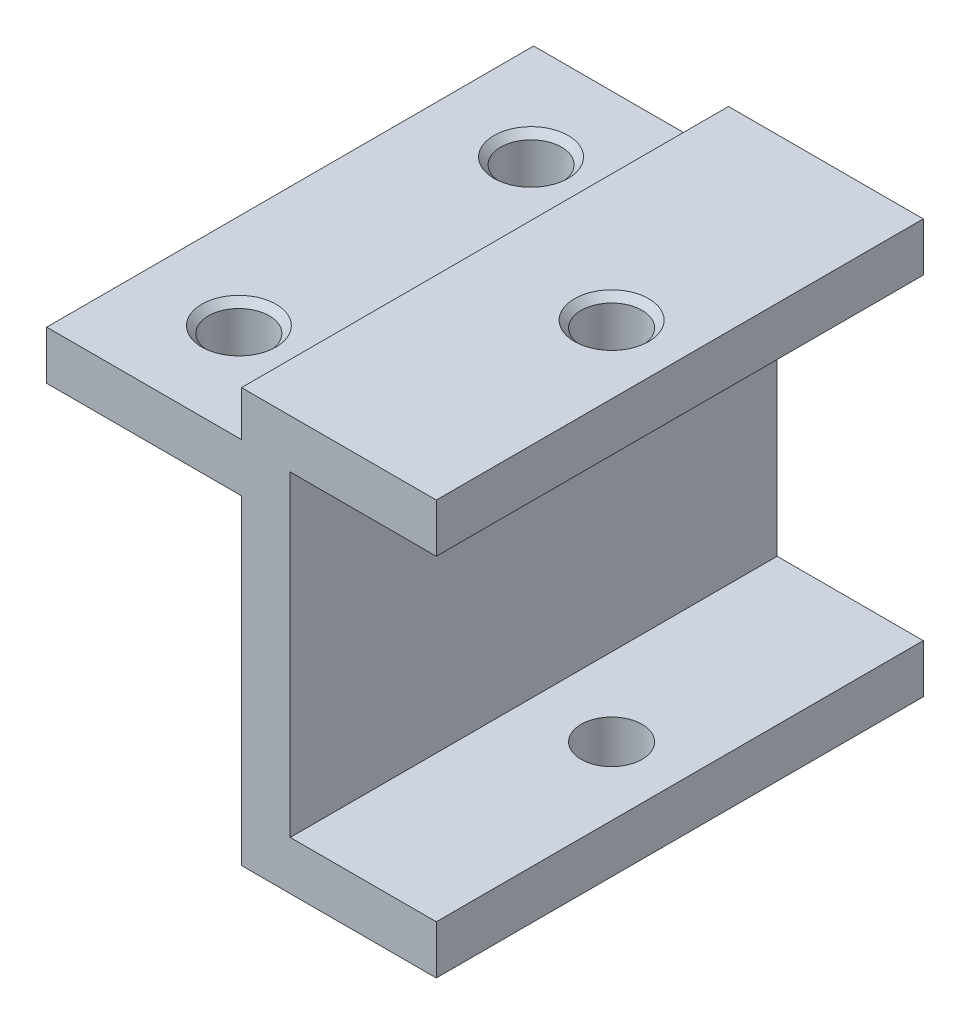
SolidWorks part; units mm, degrees
ref_plane "Front Plane" through (0, 0, 0) normal (0, 0, 1) x (1, 0, 0)
ref_plane "Top Plane" through (0, 0, 0) normal (0, 1, 0) x (1, 0, 0)
ref_plane "Right Plane" through (0, 0, 0) normal (1, 0, 0) x (0, 0, -1)
sketch "Sketch1" plane through (0, 0, 0) normal (0, 0, 1) x (1, 0, 0)
  line L0 (2, 5.1) -> (4, 5.1)
  line L1 (-4, -9.9) -> (4, -9.9)
  line L2 (-4, -9.9) -> (-4, 3.25)
  line L3 (-4, 7.1) -> (4, 7.1)
  line L7 (-2, -7.9) -> (2, -7.9)
  line L8 (-2, -7.9) -> (-2, 5.1)
  line L9 (-2, 5.1) -> (2, 5.1)
  line L10 (-4, 5.25) -> (-4, 7.1)
  line L11 (4, 5.1) -> (4, 7.1)
  line L12 (2, -7.9) -> (4, -7.9)
  line L13 (4, -7.9) -> (4, -9.9)
  line L14 (-4, 5.25) -> (-12, 5.25)
  line L16 (-4, 3.25) -> (-12, 3.25)
  line L17 (-12, 5.25) -> (-12, 3.25)
  dimension "D1" = 8
  dimension "D2" = 17
  dimension "D3" = 4
  dimension "D4" = 13
  dimension "D5" = 2
  dimension "D6" = 8
  dimension "D7" = 1.85
extrude "Boss-Extrude1" add sketch "Sketch1" along normal blind 20
sketch "Sketch2" plane through (0, 5.25, 0) normal (0, 1, 0) x (1, 0, 0)
  line L0 (-4, 0) -> (-12, 0) construction
  line L1 (-4, -20) -> (-12, -20) construction
  point P0 (-8.1084, -4)
  point P1 (-8.1084, -16)
  dimension "D1" = 4
  dimension "D2" = 4
hole_wizard "M3 Tapped Hole1" positions "3DSketch1" profile "Sketch3" tap size "M3" standard "ISO" end condition through all
sketch3d "3DSketch1"
  point P0 (-8.1084, 5.25, 4)
  point P3 (-8.1084, 5.25, 16)
sketch "Sketch3" plane through (-8.1084, 5.25, 4) normal (1, 0, 0) x (0, 0, 1)
  line L0 (0, 0) -> (0, 15.15)
  line L1 (0, 15.15) -> (1.25, 15.15)
  line L2 (1.25, 15.15) -> (1.25, 0.275)
  line L3 (1.25, 0.275) -> (1.525, 0)
  line L5 (1.525, 0) -> (0, 0)
  line L6 (-1.25, 0.275) -> (-1.525, 0) construction
  line L11 (0, -6.35) -> (0, 107.95) construction
  dimension "Thru Tap Drill Dia." = 2.5
  dimension "Thru Tap Drill Depth" = 15.15
  dimension "Near C'Sink Dia." = 3.05
  dimension "Near C'Sink Angle" = 90
cosmetic thread "Hole Thread1" parameters "D2"=3
cosmetic thread "Hole Thread2" parameters "D2"=3
sketch "Sketch4" plane through (0, 7.1, 0) normal (0, 1, 0) x (1, 0, 0)
  line L0 (4, 0) -> (-4, 0) construction
  line L1 (4, -20) -> (4, 0) construction
  point P0 (1.2, -10)
  dimension "D1" = 10
  dimension "D2" = 2.8
hole_wizard "M3 Tapped Hole2" positions "3DSketch2" profile "Sketch5" tap size "M3" standard "ISO" end condition through all
sketch3d "3DSketch2"
  point P0 (1.2, 7.1, 10)
sketch "Sketch5" plane through (1.2, 7.1, 10) normal (1, 0, 0) x (0, 0, 1)
  line L0 (0, 0) -> (0, 17)
  line L1 (0, 17) -> (1.25, 17)
  line L2 (1.25, 17) -> (1.25, 0.275)
  line L3 (1.25, 0.275) -> (1.525, 0)
  line L5 (1.525, 0) -> (0, 0)
  line L6 (-1.25, 0.275) -> (-1.525, 0) construction
  line L11 (0, -6.35) -> (0, 107.95) construction
  dimension "Thru Tap Drill Dia." = 2.5
  dimension "Thru Tap Drill Depth" = 17
  dimension "Near C'Sink Dia." = 3.05
  dimension "Near C'Sink Angle" = 90
cosmetic thread "Hole Thread3" parameters "D2"=3
